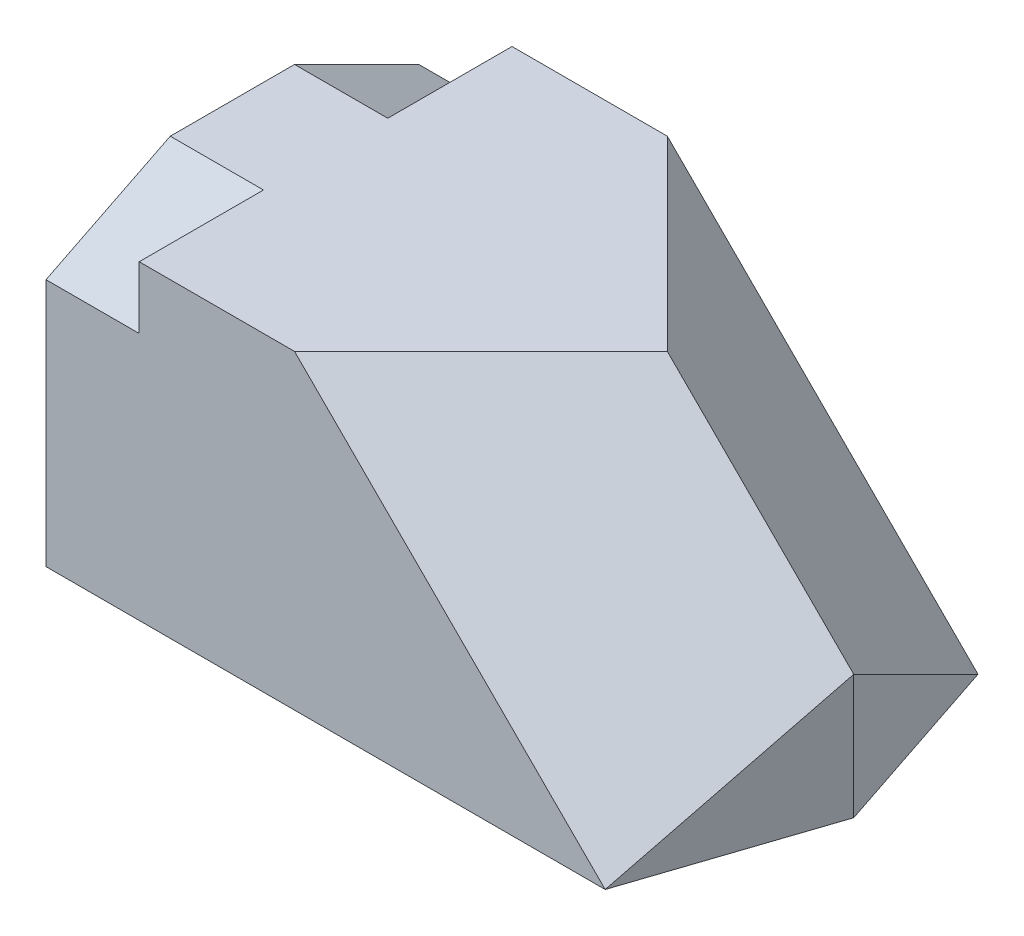
SolidWorks part; units mm, degrees
material "Alloy Steel"
ref_plane "Front Plane" through (0, 0, 0) normal (0, 0, 1) x (1, 0, 0)
ref_plane "Top Plane" through (0, 0, 0) normal (0, 1, 0) x (1, 0, 0)
ref_plane "Right Plane" through (0, 0, 0) normal (1, 0, 0) x (0, 0, -1)
sketch "Croquis2" plane through (0, 0, 0) normal (0, 0, 1) x (1, 0, 0)
  line L0 (0, 0) -> (100, 0)
  line L1 (100, 0) -> (100, 50)
  line L2 (100, 50) -> (0, 50)
  line L3 (0, 50) -> (0, 0)
  dimension "D1" = 50
  dimension "D2" = 100
extrude "Saliente-Extruir1" add sketch "Croquis2" along normal mid plane 60
sketch "Croquis4" plane through (0, 0, 0) normal (-1, 0, 0) x (0, 0, 1)
  line L0 (30, 40) -> (10, 50)
  line L1 (30, 50) -> (30, 0) construction
  line L2 (30, 50) -> (-30, 50) construction
  line L3 (10, 50) -> (30, 50)
  line L4 (30, 50) -> (30, 40)
  dimension "D1" = 20
  dimension "D2" = 10
extrude "Cortar-Extruir1" cut sketch "Croquis4" against normal blind 15 and the other way through all
sketch "Croquis6" plane through (0, 0, 0) normal (0, -1, 0) x (1, 0, 0)
  line L0 (100, 0) -> (100, 30)
  line L1 (100, 30) -> (100, -30) construction
  line L2 (100, 30) -> (90, 30)
  line L3 (0, 30) -> (100, 30) construction
  line L4 (90, 30) -> (100, 0)
  dimension "D1" = 10
extrude "Cortar-Extruir2" cut sketch "Croquis6" against normal blind 20
sketch "Croquis15" plane through (0, 0, 0) normal (0, 0, 1) x (1, 0, 0)
  line L0 (100, 20) -> (70, 50) construction
  line L1 (100, 50) -> (15, 50) construction
  dimension "D1" = 30
sketch "Croquis16" plane through (0, 50, 0) normal (0, 1, 0) x (1, 0, 0)
  line L0 (100, 0) -> (70, 0)
  line L1 (100, -30) -> (100, 30) construction
  line L2 (100, 0) -> (70, 0) construction
  line L3 (70, 0) -> (40, -30)
  line L4 (100, -30) -> (15, -30) construction
  line L5 (40, -30) -> (100, -30)
  line L6 (100, -30) -> (100, 0)
  line L7 (15, -30) -> (15, -10) construction
  dimension "D1" = 25
  dimension "D2" = 30
  dimension "D3" = 30
extrude "Cortar-Extruir3" cut sketch "Croquis16" along direction (-0.7071, 0.7071, 0) on the side against the normal through all
mirror "Simetría2" about plane through (0, 0, 0) normal (0, 0, 1) of "Cortar-Extruir3", "Cortar-Extruir2", "Cortar-Extruir1"
